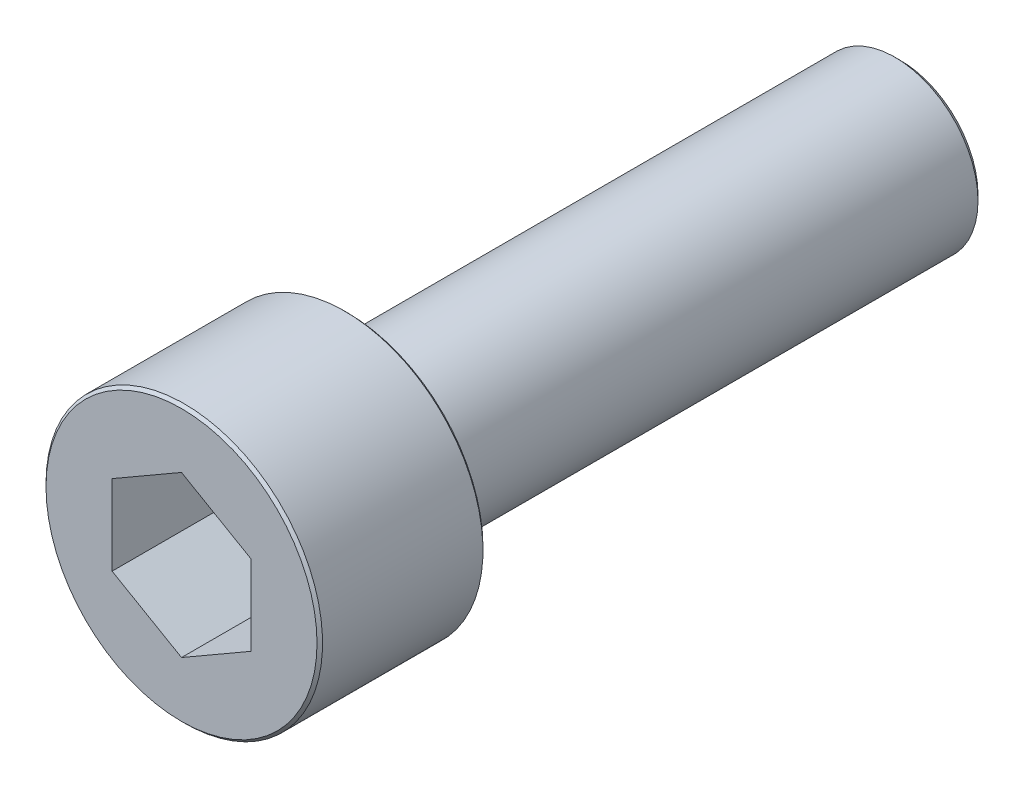
SolidWorks part; units mm, degrees
material "合金钢 (SS)"
ref_plane "前视基准面" through (0, 0, 0) normal (0, 0, 1) x (1, 0, 0)
ref_plane "上视基准面" through (0, 0, 0) normal (0, 1, 0) x (1, 0, 0)
ref_plane "右视基准面" through (0, 0, 0) normal (1, 0, 0) x (0, 0, -1)
other "Configuration Table"
sketch "草图1" plane through (0, 0, 0) normal (0, 1, 0) x (1, 0, 0)
  line L0 (5, -20) -> (0, -20)
  line L1 (0, -20) -> (0, -26)
  line L2 (0, -26) -> (5, -26)
  line L3 (5, -26) -> (5, -20)
  line L4 (0, -20) -> (0, -26) construction
revolve "旋转1" add sketch "草图1" angle 360 about L4
sketch "草图2" plane through (0, 0, 20) normal (0, 0, -1) x (-1, 0, 0)
  circle A0 centre (0, 0) radius 3
extrude "凸台-拉伸1" add sketch "草图2" along normal blind 20
sketch "草图3" plane through (0, 0, 26) normal (0, 0, 1) x (1, 0, 0)
  line L0 (-2.51, -1.4491) -> (0, -2.8983)
  line L1 (0, -2.8983) -> (2.51, -1.4491)
  line L2 (2.51, -1.4491) -> (2.51, 1.4491)
  line L3 (2.51, 1.4491) -> (0, 2.8983)
  line L4 (0, 2.8983) -> (-2.51, 1.4491)
  line L5 (-2.51, 1.4491) -> (-2.51, -1.4491)
extrude "切除-拉伸1" cut sketch "草图3" against normal blind 4.5
chamfer "倒角1" distance 0.1 angle 45 2 edges at (5, 0, 20) (5, 0, 26)
chamfer "倒角2" distance 0.2 angle 45 1 edges at (-3, 0, 0)
